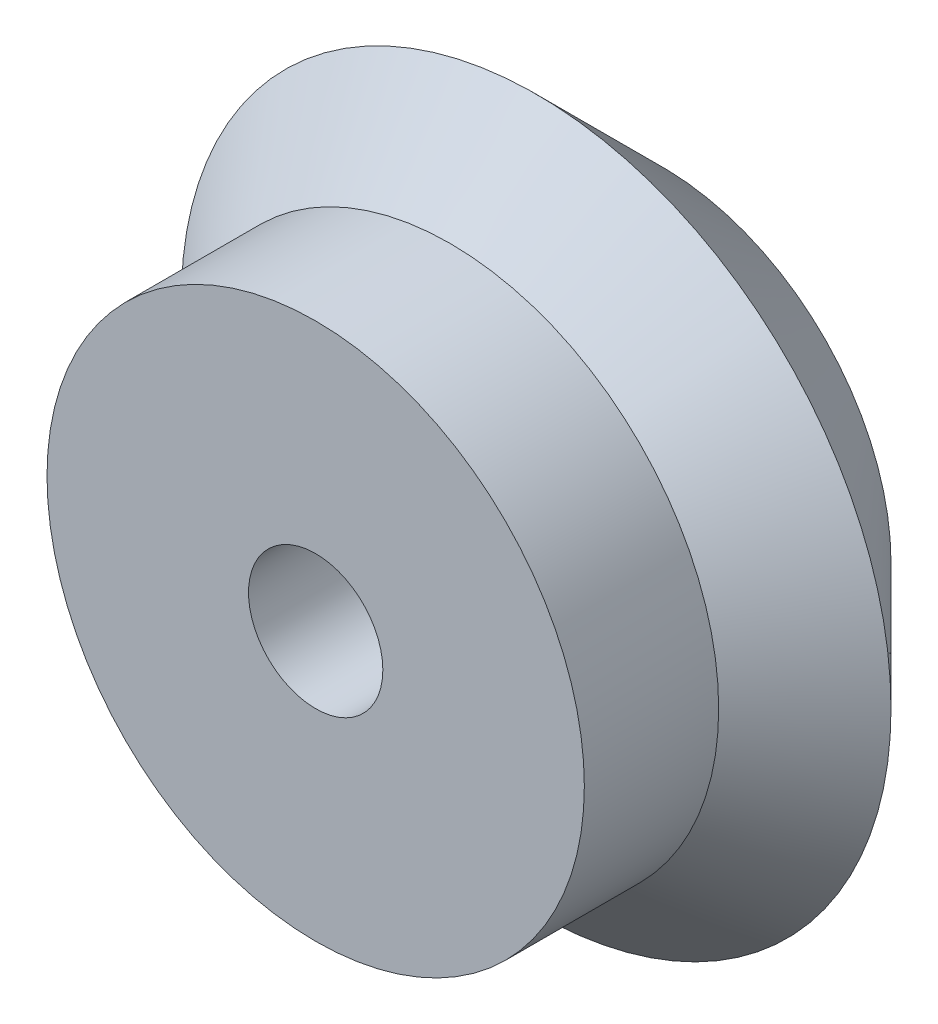
SolidWorks part; units mm, degrees
ref_plane "Front Plane" through (0, 0, 0) normal (0, 0, 1) x (1, 0, 0)
ref_plane "Top Plane" through (0, 0, 0) normal (0, 1, 0) x (1, 0, 0)
ref_plane "Right Plane" through (0, 0, 0) normal (1, 0, 0) x (0, 0, -1)
sketch "Sketch1" plane through (0, 0, 0) normal (0, 0, 1) x (1, 0, 0)
  circle A0 centre (0, 0) radius 30
  circle A1 centre (0, 0) radius 7.5
  dimension "D1" = 60
  dimension "D2" = 15
extrude "Boss-Extrude1" add sketch "Sketch1" along normal blind 15
sketch "Sketch2" plane through (0, 0, 0) normal (0, 1, 0) x (1, 0, 0)
  line L0 (30, 0) -> (39.62, 9.62)
  line L1 (30, 0) -> (57.0538, 0) construction
  line L2 (0, 0) -> (0, 25.6505) construction
  line L3 (-30, 0) -> (-39.62, 9.62)
  line L4 (39.62, 9.62) -> (25.4779, 23.7621)
  line L5 (25.4779, 23.7621) -> (17.9678, 17)
  line L6 (17.9678, 17) -> (-17.9678, 17)
  line L7 (-30, -15) -> (30, -15) construction
  line L8 (-25.4779, 23.7621) -> (-17.9678, 17)
  line L9 (-39.62, 9.62) -> (-25.4779, 23.7621)
  line L10 (30, 0) -> (-30, 0)
  line L11 (7.5, 17) -> (7.5, 0)
  point P18 (0, 17)
  dimension "D1" = 45
  dimension "D2" = 79.24
  dimension "D3" = 20
  dimension "D4" = 24.62
  dimension "D5" = 42
  dimension "D6" = 32
  dimension "D7" = 7.5
revolve "Revolve4" add sketch "Sketch2" angle 360 about L2
